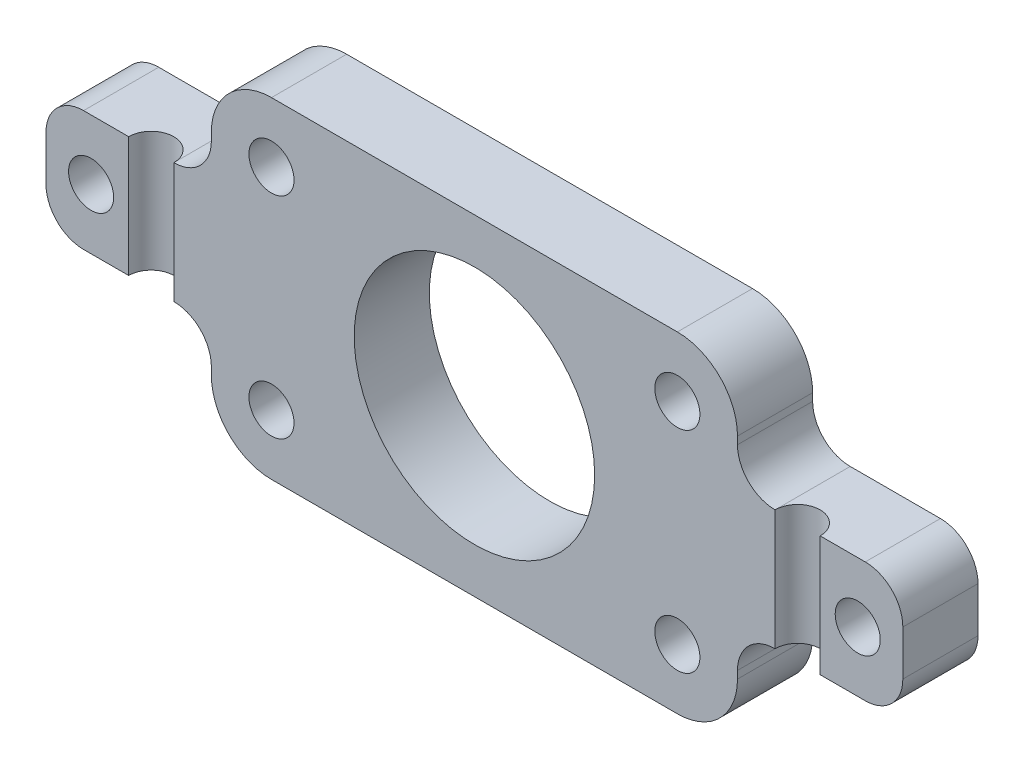
SolidWorks part; units mm, degrees
material "POM 乙缩醛共聚物"
ref_plane "前视基准面" through (0, 0, 0) normal (0, 0, 1) x (1, 0, 0)
ref_plane "上视基准面" through (0, 0, 0) normal (0, 1, 0) x (1, 0, 0)
ref_plane "右视基准面" through (0, 0, 0) normal (1, 0, 0) x (0, 0, -1)
sketch "草图1" plane through (0, 0, 0) normal (0, 0, 1) x (1, 0, 0)
  line L0 (0, 11) -> (57, 11) construction
  line L1 (0, 0) -> (57, 0) construction
  line L2 (0, 0) -> (0, 22) construction
  line L3 (0, 22) -> (57, 22) construction
  line L4 (57, 0) -> (57, 22) construction
  line L5 (2.5, 15) -> (8.5, 15)
  line L6 (11, 17.5) -> (11, 18)
  line L7 (28.5, 22) -> (28.5, 0) construction
  line L8 (11, 4.5) -> (11, 4)
  line L9 (2.5, 7) -> (8.5, 7)
  line L10 (46, 4.5) -> (46, 4)
  line L11 (54.5, 7) -> (48.5, 7)
  line L12 (46, 17.5) -> (46, 18)
  line L13 (54.5, 15) -> (48.5, 15)
  line L14 (0, 12.5) -> (0, 9.5)
  line L15 (15, 0) -> (42, 0)
  line L16 (57, 9.5) -> (57, 12.5)
  line L17 (42, 22) -> (15, 22)
  circle A0 centre (28.5, 11) radius 8
  arc A1 (11, 4) -> (15, 0) centre (15, 4) ccw
  arc A2 (46, 4) -> (42, 0) centre (42, 4) cw
  arc A3 (46, 18) -> (42, 22) centre (42, 18) ccw
  arc A4 (11, 18) -> (15, 22) centre (15, 18) cw
  arc A5 (54.5, 7) -> (57, 9.5) centre (54.5, 9.5) ccw
  arc A6 (54.5, 15) -> (57, 12.5) centre (54.5, 12.5) cw
  arc A7 (2.5, 7) -> (0, 9.5) centre (2.5, 9.5) cw
  arc A8 (2.5, 15) -> (0, 12.5) centre (2.5, 12.5) ccw
  arc A9 (11, 4.5) -> (8.5, 7) centre (8.5, 4.5) ccw
  arc A10 (46, 4.5) -> (48.5, 7) centre (48.5, 4.5) cw
  arc A11 (46, 17.5) -> (48.5, 15) centre (48.5, 17.5) ccw
  arc A12 (8.5, 15) -> (11, 17.5) centre (8.5, 17.5) ccw
  circle A13 centre (15, 18) radius 1.5
  circle A14 centre (15, 4) radius 1.5
  circle A15 centre (42, 18) radius 1.5
  circle A16 centre (42, 4) radius 1.5
  circle A17 centre (3, 11) radius 1.5
  circle A18 centre (28.5, 11) radius 8.5 construction
  circle A19 centre (15, 18) radius 3 construction
  circle A20 centre (3, 11) radius 3 construction
  circle A21 centre (54, 11) radius 1.5
  point P25 (11, 0)
  point P28 (46, 0)
  point P31 (46, 22)
  point P34 (11, 22)
  point P37 (57, 7)
  point P40 (57, 15)
  point P43 (0, 7)
  point P46 (0, 15)
  point P49 (11, 7)
  point P52 (46, 7)
  point P55 (46, 15)
  point P58 (11, 15)
  dimension "D3" = 16
  dimension "D4" = 4
  dimension "D6" = 4
  dimension "D7" = 2.5
  dimension "D8" = 3
  dimension "D9" = 3
  dimension "D10" = 3
  dimension "D11" = 17
  dimension "D12" = 6
  dimension "D13" = 6
  dimension "D1" = 22
  dimension "D2" = 57
  dimension "D5" = 11
extrude "凸台-拉伸1" add sketch "草图1" along normal blind 5
sketch "草图2" plane through (0, 15, 0) normal (0, 1, 0) x (1, 0, 0)
  line L0 (8.5, -5) -> (2.5, -5) construction
  line L1 (28.5, 0) -> (28.5, -5) construction
  line L2 (42, 0) -> (15, 0) construction
  line L3 (42, -5) -> (15, -5) construction
  circle A0 centre (7, -5) radius 1.5
  circle A1 centre (50, -5) radius 1.5
  dimension "D1" = 3
  dimension "D2" = 7
extrude "切除-拉伸1" cut sketch "草图2" against normal blind 11.5
chamfer "倒角1" distance 2 angle 45 4 edges at (40.5, 18, 0) (43.5, 4, 0) (16.5, 18, 0) (13.5, 4, 0)
